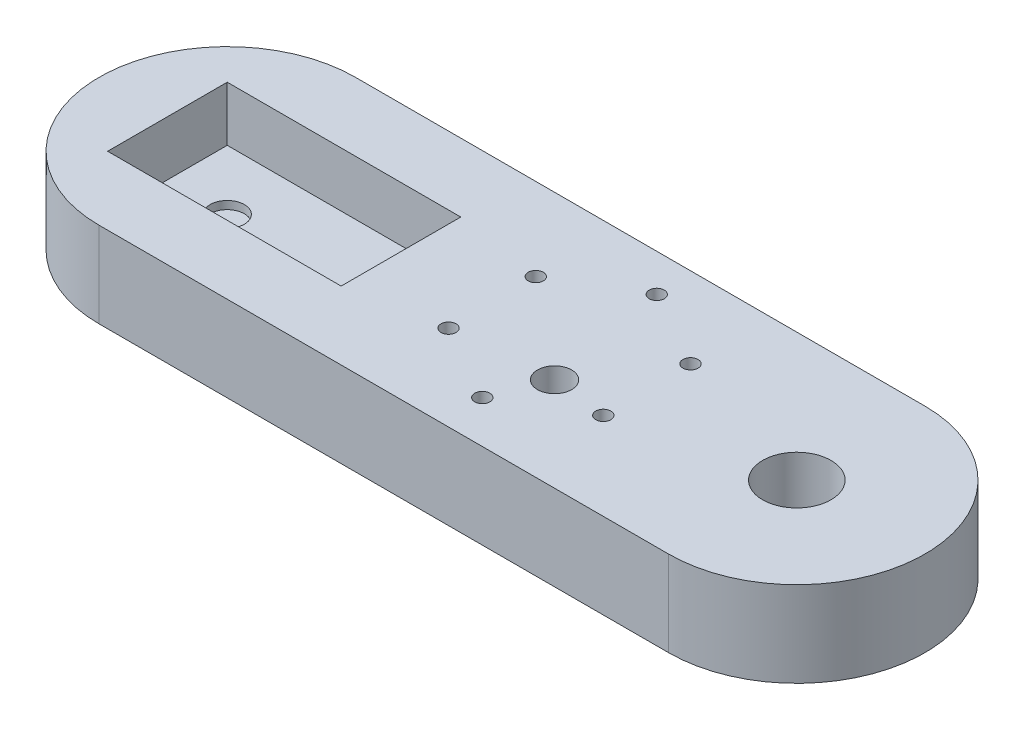
SolidWorks part; units mm, degrees
material "ABS"
ref_plane "Front Plane" through (0, 0, 0) normal (0, 0, 1) x (1, 0, 0)
ref_plane "Top Plane" through (0, 0, 0) normal (0, 1, 0) x (1, 0, 0)
ref_plane "Right Plane" through (0, 0, 0) normal (1, 0, 0) x (0, 0, -1)
sketch "Sketch1" plane through (0, 0, 0) normal (0, 1, 0) x (1, 0, 0)
  line L0 (0, 0) -> (100, 0) construction
  line L1 (0, 22.5) -> (100, 22.5)
  line L2 (0, -22.5) -> (100, -22.5)
  arc A0 (0, 22.5) -> (0, -22.5) centre (0, 0) ccw
  arc A1 (100, -22.5) -> (100, 22.5) centre (100, 0) ccw
  point P3 (50, 0)
  dimension "D1" = 100
  dimension "D2" = 45
extrude "Boss-Extrude1" add sketch "Sketch1" along normal blind 15
sketch "Sketch2" plane through (0, 0, 0) normal (0, -1, 0) x (1, 0, 0)
  circle A0 centre (0, 0) radius 10
  dimension "D1" = 20
extrude "Boss-Extrude2" add sketch "Sketch2" along normal blind 9
sketch "Sketch3" plane through (0, 15, 0) normal (0, 1, 0) x (1, 0, 0)
  circle A0 centre (0, 0) radius 3
  dimension "D1" = 6
extrude "Cut-Extrude1" cut sketch "Sketch3" against normal up to surface (15 mm away)
sketch "Sketch4" plane through (0, 15, 0) normal (0, 1, 0) x (1, 0, 0)
  line L1 (30.5, -10.5) -> (-10.5, -10.5)
  line L2 (30.5, -10.5) -> (30.5, 10.5)
  line L3 (30.5, 10.5) -> (-10.5, 10.5)
  line L4 (-10.5, -10.5) -> (-10.5, 10.5)
  point P4 (-10.5, 0)
  point P6 (0, 0)
  dimension "D1" = 21
  dimension "D2" = 41
  dimension "D3" = 10.5
extrude "Cut-Extrude2" cut sketch "Sketch4" against normal blind 9.6 contours L3 L4 L1 L2
ref_plane "Plane1" through (-22.5, 15, 0) normal (-1, 0, 0) x (0, 0, 1)
sketch "Sketch5" plane through (-22.5, 15, 0) normal (-1, 0, 0) x (0, 0, 1)
  line L1 (-12.5, -11) -> (12.5, -11)
  line L2 (-12.5, -11) -> (-12.5, -15)
  line L3 (-12.5, -15) -> (12.5, -15)
  line L4 (12.5, -11) -> (12.5, -15)
  line L6 (22.5, 0) -> (22.5, -15) construction
  point P4 (0, -11)
  dimension "D1" = 4
  dimension "D2" = 25
extrude "Cut-Extrude3" cut sketch "Sketch5" against normal blind 25
sketch "Sketch6" plane through (0, 15, 0) normal (0, 1, 0) x (1, 0, 0)
  circle A0 centre (100, 0) radius 6
  dimension "D1" = 12
extrude "Cut-Extrude4" cut sketch "Sketch6" against normal through all both and the other way through all
sketch "Sketch7" plane through (0, 15, 0) normal (0, 1, 0) x (1, 0, 0)
  circle A0 centre (63.4807, -6.0093) radius 3 construction
  circle A1 centre (63.4807, -6.0093) radius 3
extrude "Cut-Extrude5" cut sketch "Sketch7" against normal through all
sketch "Sketch8" plane through (0, 0, 0) normal (0, -1, 0) x (1, 0, 0)
  circle A0 centre (46.1391, -8.0308) radius 1.325 construction
  circle A1 centre (46.3234, 7.4682) radius 1.325 construction
  circle A2 centre (59.838, 15.058) radius 1.325 construction
  circle A3 centre (73.1683, 7.149) radius 1.325 construction
  circle A4 centre (72.984, -8.3499) radius 1.325 construction
  circle A5 centre (59.4695, -15.9398) radius 1.325 construction
  circle A6 centre (46.1391, -8.0308) radius 1.325
  circle A7 centre (46.3234, 7.4682) radius 1.325
  circle A8 centre (59.838, 15.058) radius 1.325
  circle A9 centre (73.1683, 7.149) radius 1.325
  circle A10 centre (72.984, -8.3499) radius 1.325
  circle A11 centre (59.4695, -15.9398) radius 1.325
extrude "Cut-Extrude6" cut sketch "Sketch8" against normal through all
